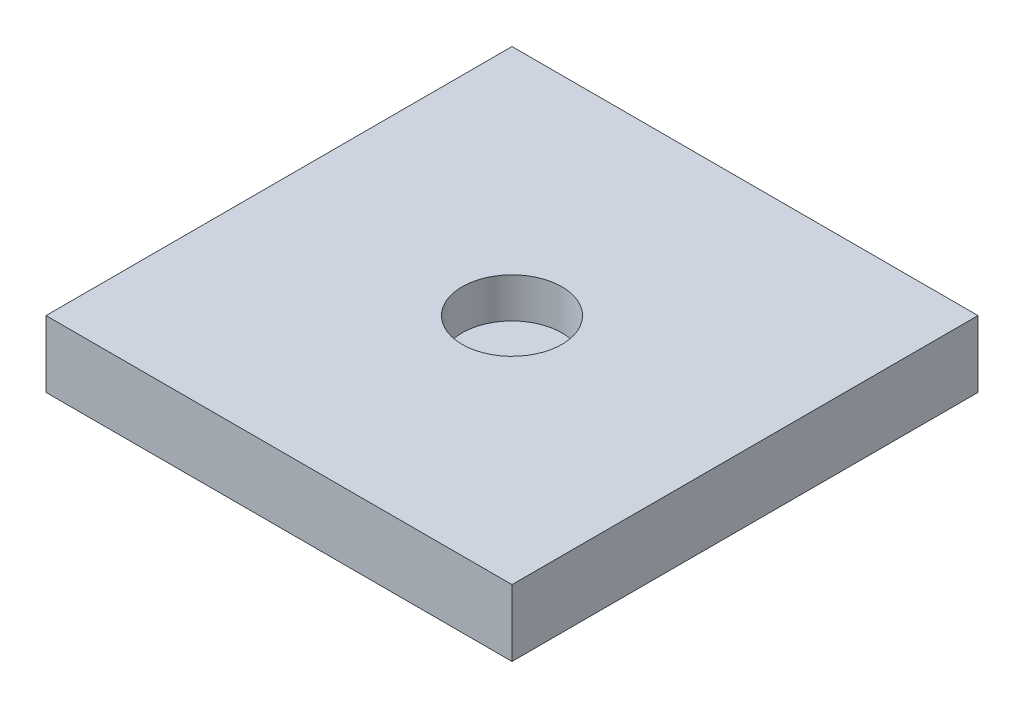
SolidWorks part; units mm, degrees
ref_plane "前视基准面" through (0, 0, 0) normal (0, 0, 1) x (1, 0, 0)
ref_plane "上视基准面" through (0, 0, 0) normal (0, 1, 0) x (1, 0, 0)
ref_plane "右视基准面" through (0, 0, 0) normal (1, 0, 0) x (0, 0, -1)
other "Configuration Table"
sketch "草图1" plane through (0, 0, 0) normal (0, 1, 0) x (1, 0, 0)
  line L1 (-17.5, 17.5) -> (17.5, 17.5)
  line L2 (-17.5, 17.5) -> (-17.5, -17.5)
  line L3 (-17.5, -17.5) -> (17.5, -17.5)
  line L4 (17.5, 17.5) -> (17.5, -17.5)
  line L5 (-17.5, 17.5) -> (17.5, -17.5) construction
  line L6 (-17.5, -17.5) -> (17.5, 17.5) construction
  point P0 (0, 0)
  dimension "D1" = 35
  dimension "D2" = 35
extrude "凸台-拉伸1" add sketch "草图1" along normal blind 5
sketch "草图2" plane through (0, 5, 0) normal (0, 1, 0) x (1, 0, 0)
  circle A0 centre (0, 0) radius 3.75
  dimension "D1" = 7.5
extrude "切除-拉伸1" cut sketch "草图2" against normal blind 3
